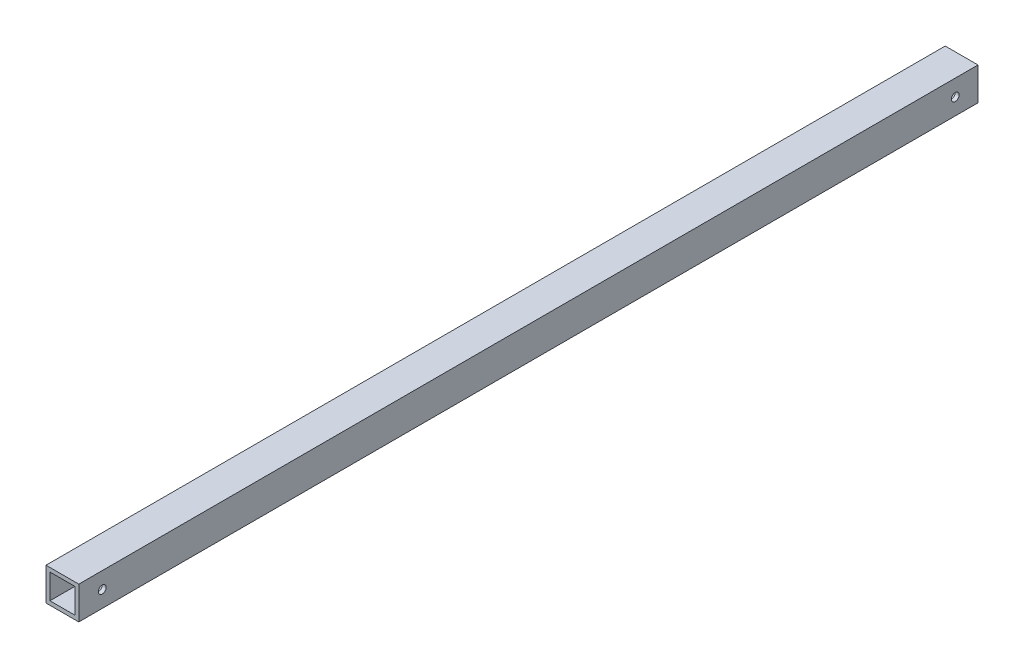
SolidWorks part; units mm, degrees
ref_plane "前视基准面" through (0, 0, 0) normal (0, 0, 1) x (1, 0, 0)
ref_plane "上视基准面" through (0, 0, 0) normal (0, 1, 0) x (1, 0, 0)
ref_plane "右视基准面" through (0, 0, 0) normal (1, 0, 0) x (0, 0, -1)
sketch "草图1" plane through (0, 0, 0) normal (0, 0, 1) x (1, 0, 0)
  line L1 (0, 0) -> (25, 0)
  line L2 (0, 0) -> (0, -25)
  line L3 (0, -25) -> (25, -25)
  line L4 (25, 0) -> (25, -25)
  line L5 (3, -3) -> (22, -3)
  line L6 (3, -3) -> (3, -22)
  line L7 (3, -22) -> (22, -22)
  line L8 (22, -3) -> (22, -22)
  dimension "D1" = 3
  dimension "D2" = 3
  dimension "D3" = 3
  dimension "D4" = 3
  dimension "D5" = 25
  dimension "D6" = 25
extrude "拉伸1" add sketch "草图1" along normal blind 685.5
hole_wizard "Ø6.0 (6) 直径孔1" positions "草图3" profile "草图4" hole size "Ø6.0" standard "GB" end condition through all
sketch "草图3" plane through (25, 0, 0) normal (1, 0, 0) x (0, 0, -1)
  line L0 (-685.5, -25) -> (-685.5, 0) construction
  line L1 (-685.5, -25) -> (0, -25) construction
  point P1 (-667.65, -12.5)
  dimension "D1" = 17.85
  dimension "D3" = 12.5
sketch "草图4" plane through (25, -12.5, 667.65) normal (0, 1, 0) x (0, 0, -1)
  line L0 (0, 0) -> (0, 25)
  line L1 (0, 25) -> (3, 25)
  line L2 (3, 25) -> (3, 0)
  line L5 (3, 0) -> (0, 0)
  line L11 (0, -6.35) -> (0, 107.95) construction
  dimension "通孔孔直径" = 6
  dimension "通孔孔深度" = 25
sketch "草图5" plane through (0, 0, 0) normal (-1, 0, 0) x (0, 0, 1)
  circle A0 centre (667.65, -12.5) radius 6
  circle A2 centre (667.65, -12.5) radius 3 construction
  dimension "D1" = 12
extrude "切除-拉伸1" cut sketch "草图5" against normal up to next
pattern_linear "阵列(线性)1" count 2 spacing 650.3 along (0, 0, -1) of "Ø6.0 (6) 直径孔1", "切除-拉伸1"
